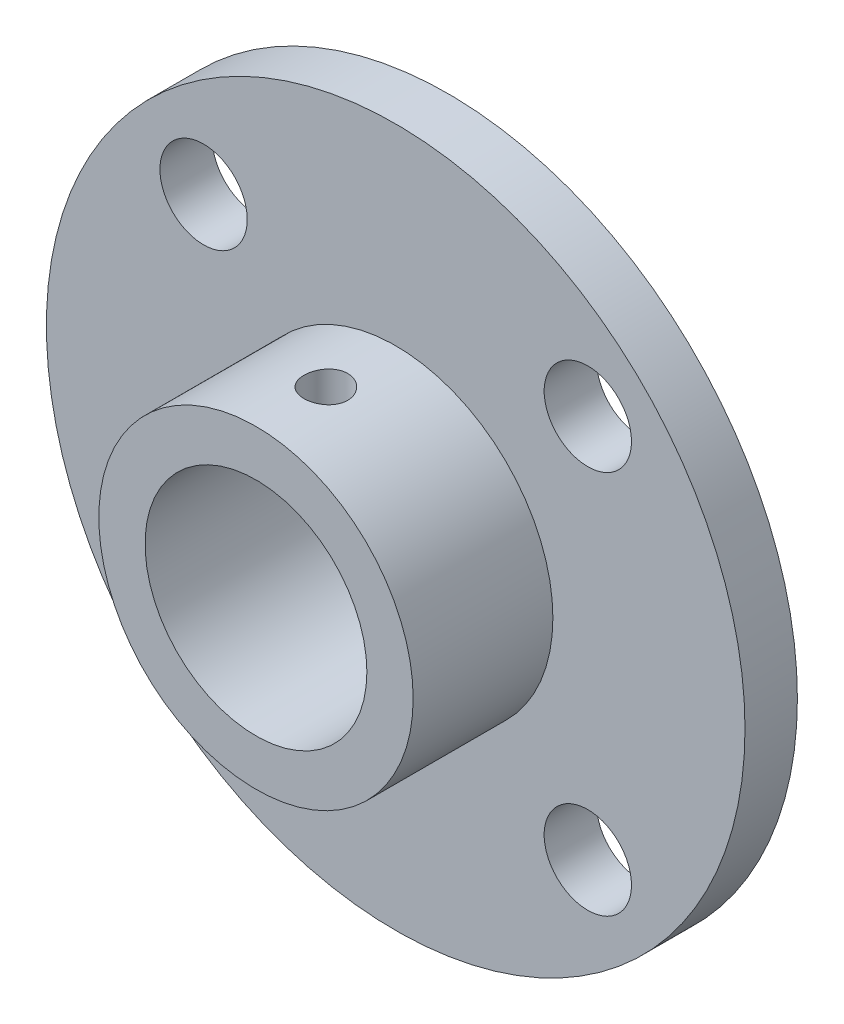
SolidWorks part; units mm, degrees
ref_plane "Front Plane" through (0, 0, 0) normal (0, 0, 1) x (1, 0, 0)
ref_plane "Top Plane" through (0, 0, 0) normal (0, 1, 0) x (1, 0, 0)
ref_plane "Right Plane" through (0, 0, 0) normal (1, 0, 0) x (0, 0, -1)
sketch "Sketch1" plane through (0, 0, 0) normal (0, 0, 1) x (1, 0, 0)
  circle A0 centre (0, 0) radius 20
  dimension "D1" = 40
extrude "Boss-Extrude1" add sketch "Sketch1" along normal blind 3
sketch "Sketch2" plane through (0, 0, 3) normal (0, 0, 1) x (1, 0, 0)
  circle A0 centre (0, 0) radius 9
  dimension "D1" = 18
extrude "Boss-Extrude2" add sketch "Sketch2" along normal blind 8
sketch "Sketch4" plane through (0, 0, 11) normal (0, 0, 1) x (1, 0, 0)
  circle A0 centre (0, 0) radius 6.35
  dimension "D1" = 12.7
extrude "Cut-Extrude1" cut sketch "Sketch4" against normal through all
ref_plane "Plane2" through (0, 0, 7) normal (0, 0, 1) x (1, 0, 0)
hole_wizard "M3 Tapped Hole1" positions "3DSketch7" profile "Sketch15" tap size "M3" standard "ISO"
sketch3d "3DSketch7"
  point P0 (0, 9, 7)
  dimension "D1" = 4
sketch "Sketch15" plane through (0, 9, 7) normal (1, 0, 0) x (0, 0, 1)
  line L0 (0, 0) -> (0, 2.65)
  line L1 (0, 2.65) -> (1.25, 2.65)
  line L2 (1.25, 2.65) -> (1.25, 0)
  line L5 (1.25, 0) -> (0, 0)
  line L11 (0, -6.35) -> (0, 107.95) construction
  dimension "Thru Tap Drill Dia." = 2.5
  dimension "Thru Tap Drill Depth" = 2.65
cosmetic thread "Hole Thread1" parameters "D2"=3
sketch "Sketch16" plane through (0, 0, 3) normal (0, 0, 1) x (1, 0, 0)
  line L0 (0, 0) -> (34.2865, 0) construction
  line L1 (0, 0) -> (11, 11) construction
  point P0 (11, 11)
  dimension "D1" = 11
  dimension "D2" = 45
hole_wizard "Ø5.0 (5) Diameter Hole1" positions "3DSketch8" profile "Sketch17" hole size "Ø5.0" standard "ISO" end condition through all
sketch3d "3DSketch8"
  point P0 (11, 11, 3)
sketch "Sketch17" plane through (11, 11, 3) normal (1, 0, 0) x (0, -1, 0)
  line L0 (0, 0) -> (0, 3)
  line L1 (0, 3) -> (2.5, 3)
  line L2 (2.5, 3) -> (2.5, 0)
  line L5 (2.5, 0) -> (0, 0)
  line L11 (0, -6.35) -> (0, 107.95) construction
  dimension "Thru Hole Dia." = 5
  dimension "Thru Hole Depth" = 3
pattern_circular "CirPattern1" count 4 over 360 about axis through (0, 0, 0) along (0, 0, 1) of "Ø5.0 (5) Diameter Hole1"
